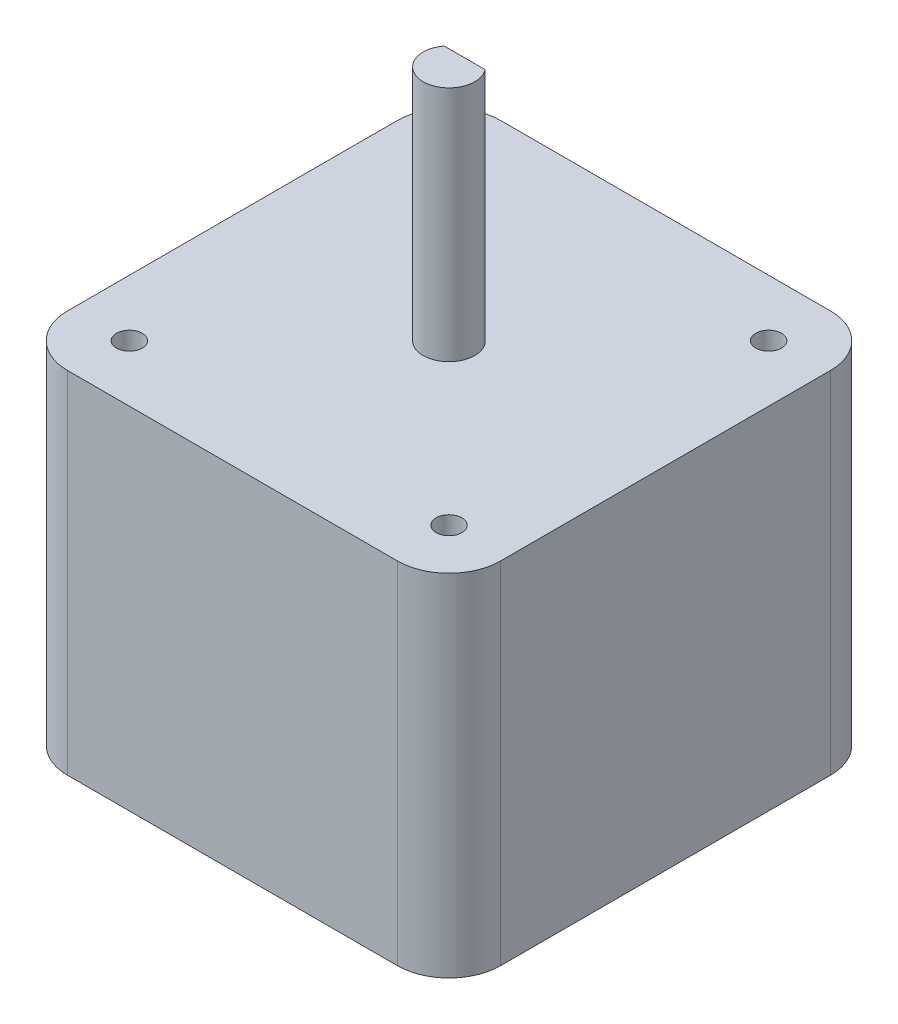
SolidWorks part; units mm, degrees
ref_plane "前视基准面" through (0, 0, 0) normal (0, 0, 1) x (1, 0, 0)
ref_plane "上视基准面" through (0, 0, 0) normal (0, 1, 0) x (1, 0, 0)
ref_plane "右视基准面" through (0, 0, 0) normal (1, 0, 0) x (0, 0, -1)
sketch "草图1" plane through (0, 0, 0) normal (0, 1, 0) x (1, 0, 0)
  line L1 (-21, -21) -> (21, -21)
  line L2 (-21, -21) -> (-21, 21)
  line L3 (-21, 21) -> (21, 21)
  line L4 (21, -21) -> (21, 21)
  line L5 (-21, -21) -> (21, 21) construction
  line L6 (-21, 21) -> (21, -21) construction
  point P0 (0, 0)
  dimension "D1" = 42
  dimension "D2" = 42
extrude "凸台-拉伸1" add sketch "草图1" along normal blind 34
hole_wizard "M3 螺纹孔1" positions "草图2" profile "草图4" tap size "M3" standard "GB"
sketch "草图2" plane through (0, 34, 0) normal (0, 1, 0) x (1, 0, 0)
  line L1 (-15.5, 15.5) -> (15.5, 15.5)
  line L2 (-15.5, 15.5) -> (-15.5, -15.5)
  line L3 (-15.5, -15.5) -> (15.5, -15.5)
  line L4 (15.5, 15.5) -> (15.5, -15.5)
  point P1 (-15.5, 15.5)
  point P2 (15.5, -15.5)
  point P93 (-15.5, -15.5)
  point P94 (15.5, 15.5)
  point P96 (0, 15.5)
  point P98 (-15.5, 0)
  dimension "D1" = 31
  dimension "D2" = 31
sketch "草图4" plane through (-15.5, 34, -15.5) normal (1, 0, 0) x (0, 0, 1)
  line L0 (0, 0) -> (0, 5.7511)
  line L1 (0, 5.7511) -> (1.25, 5)
  line L2 (1.25, 5) -> (1.25, 0)
  line L5 (1.25, 0) -> (0, 0)
  line L10 (0, 5.7511) -> (-1.25, 5) construction
  line L11 (0, -6.35) -> (0, 107.95) construction
  dimension "螺纹孔钻头直径" = 2.5
  dimension "螺纹孔钻头深度" = 5
  dimension "导头角度" = 118
cosmetic thread "孔螺蚊线1" parameters "D1"=6, "D2"=3
cosmetic thread "孔螺蚊线2" parameters "D1"=6, "D2"=3
cosmetic thread "孔螺蚊线3" parameters "D1"=6, "D2"=3
cosmetic thread "孔螺蚊线4" parameters "D1"=6, "D2"=3
sketch "草图5" plane through (0, 34, 0) normal (0, 1, 0) x (1, 0, 0)
  line L0 (-1.9846, 1.5204) -> (1.9846, 1.5204)
  circle A0 centre (0, 0) radius 2.5
  dimension "D1" = 5
extrude "凸台-拉伸2" add sketch "草图5" along normal blind 23 contours L0 A0
fillet "圆角1" radius 5 4 edges at (-21, 17, -21) (-21, 17, 21) (21, 17, 21) (21, 17, -21)
